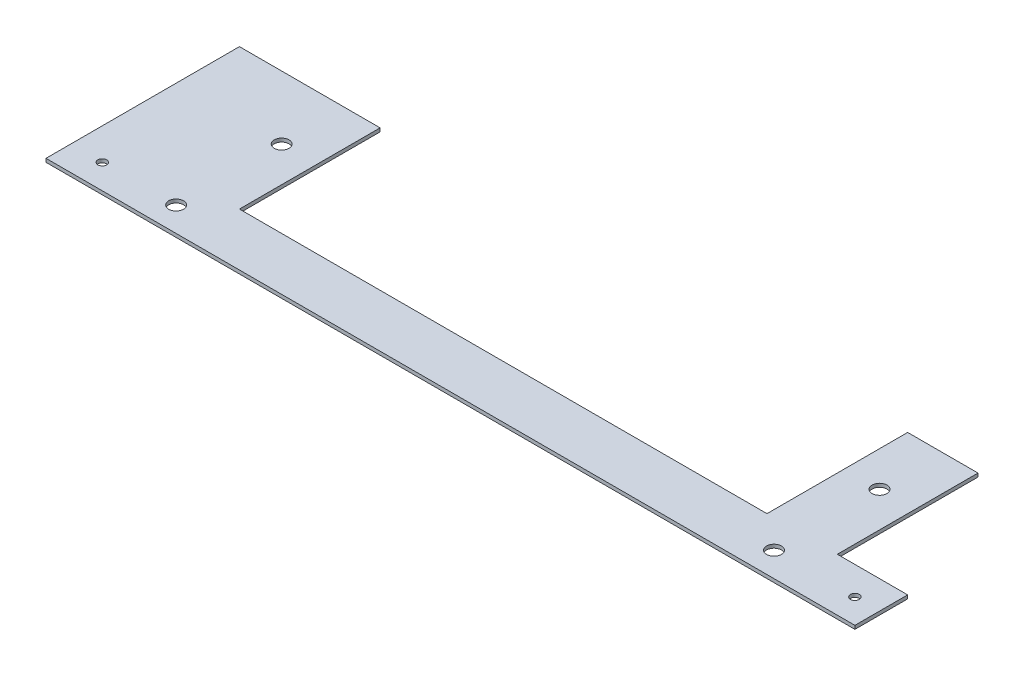
SolidWorks part; units mm, degrees
ref_plane "正面" through (0, 0, 0) normal (0, 0, 1) x (1, 0, 0)
ref_plane "平面" through (0, 0, 0) normal (0, 1, 0) x (1, 0, 0)
ref_plane "右側面" through (0, 0, 0) normal (1, 0, 0) x (0, 0, -1)
sketch "ｽｹｯﾁ1" plane through (0, 0, 0) normal (0, 0, 1) x (1, 0, 0)
  line L1 (0, 0) -> (230, 0)
  line L2 (0, 0) -> (0, 1)
  line L3 (0, 1) -> (230, 1)
  line L4 (230, 0) -> (230, 1)
  dimension "D1" = 1
  dimension "D2" = 230
extrude "ﾎﾞｽ - 押し出し1" add sketch "ｽｹｯﾁ1" along normal blind 15
hole_wizard "M3x0.5 ねじ穴1" positions "ｽｹｯﾁ2" profile "ｽｹｯﾁ3" tap size "M3x0.5" standard "JIS" end condition through all
sketch "ｽｹｯﾁ2" plane through (0, 0, 0) normal (0, -1, 0) x (-1, 0, 0)
  line L0 (0, -15) -> (0, 0) construction
  line L1 (-230, -15) -> (-230, 0) construction
  line L2 (-0.55, 0) -> (0.55, 0) construction
  point P0 (-9, -8)
  point P2 (-223, -8)
  point P9 (-230, -7.5)
  dimension "D1" = 9
  dimension "D2" = 7
  dimension "D3" = 8
  dimension "D4" = 8
sketch "ｽｹｯﾁ3" plane through (9, 0, 8) normal (1, 0, 0) x (0, 0, -1)
  line L0 (0, 0) -> (0, 1)
  line L1 (0, 1) -> (1.25, 1)
  line L2 (1.25, 1) -> (1.25, 0)
  line L5 (1.25, 0) -> (0, 0)
  line L11 (0, -6.35) -> (0, 107.95) construction
  dimension "次ｻｰﾌｪｽまでのねじ下穴ﾄﾞﾘﾙ直径" = 2.5
  dimension "次ｻｰﾌｪｽまでのねじ下穴ﾄﾞﾘﾙの深さ" = 1
cosmetic thread "穴のねじ山1" parameters "D2"=3
cosmetic thread "穴のねじ山2" parameters "D2"=3
hole_wizard "M5x0.8 ねじ穴1" positions "ｽｹｯﾁ4" profile "ｽｹｯﾁ5" tap size "M5x0.8" standard "JIS" end condition through all
sketch "ｽｹｯﾁ4" plane through (0, 1, 0) normal (0, 1, 0) x (1, 0, 0)
  line L0 (230, -15) -> (230, 0) construction
  line L1 (0, -15) -> (0, 0) construction
  line L2 (230, -15) -> (0, -15) construction
  point P0 (30, -8)
  point P2 (200, -8)
  dimension "D1" = 30
  dimension "D2" = 30
  dimension "D3" = 7
  dimension "D4" = 7
cosmetic thread "穴のねじ山3" parameters "D2"=5
cosmetic thread "穴のねじ山4" parameters "D2"=5
sketch "ｽｹｯﾁ5" plane through (30, 1, 8) normal (1, 0, 0) x (0, 0, 1)
  line L0 (0, 0) -> (0, 1)
  line L1 (0, 1) -> (2.1, 1)
  line L2 (2.1, 1) -> (2.1, 0)
  line L5 (2.1, 0) -> (0, 0)
  line L11 (0, -6.35) -> (0, 107.95) construction
  dimension "次ｻｰﾌｪｽまでのねじ下穴ﾄﾞﾘﾙ直径" = 4.2
  dimension "次ｻｰﾌｪｽまでのねじ下穴ﾄﾞﾘﾙの深さ" = 1
sketch "ｽｹｯﾁ10" plane through (0, 0, 0) normal (0, 0, -1) x (-1, 0, 0)
  line L0 (-230, 1) -> (0, 1) construction
  line L1 (-210, 1) -> (-190, 1)
  line L2 (-210, 1) -> (-210, 0)
  line L3 (-210, 0) -> (-190, 0)
  line L4 (-190, 1) -> (-190, 0)
  line L5 (0, 0) -> (-230, 0) construction
  line L6 (-230, 0) -> (-230, 1) construction
  point P10 (-230, 0.5)
  dimension "D1" = 20
  dimension "D2" = 20
extrude "ﾎﾞｽ - 押し出し3" add sketch "ｽｹｯﾁ10" along normal blind 40
sketch "ｽｹｯﾁ11" plane through (0, 0, 0) normal (0, 0, -1) x (-1, 0, 0)
  line L0 (0, 1) -> (0, 0) construction
  line L1 (0, 1) -> (-40, 1)
  line L2 (0, 1) -> (0, 0)
  line L3 (0, 0) -> (-40, 0)
  line L4 (-40, 1) -> (-40, 0)
  line L5 (0, 0) -> (-190, 0) construction
  dimension "D1" = 40
extrude "ﾎﾞｽ - 押し出し4" add sketch "ｽｹｯﾁ11" along normal blind 40
hole_wizard "M5x0.8 ねじ穴3" positions "ｽｹｯﾁ12" profile "ｽｹｯﾁ13" tap size "M5x0.8" standard "JIS" end condition through all
sketch "ｽｹｯﾁ12" plane through (0, 1, 0) normal (0, 1, 0) x (1, 0, 0)
  line L0 (40, 40) -> (40, 0) construction
  line L1 (190, 40) -> (190, 0) construction
  circle A0 centre (30, -8) radius 2.1 construction
  circle A1 centre (200, -8) radius 2.1 construction
  point P0 (30, 22)
  point P2 (200, 22)
  dimension "D2" = 30
  dimension "D1" = 10
  dimension "D3" = 30
  dimension "D4" = 10
sketch "ｽｹｯﾁ13" plane through (30, 1, -22) normal (1, 0, 0) x (0, 0, 1)
  line L0 (0, 0) -> (0, 1)
  line L1 (0, 1) -> (2.1, 1)
  line L2 (2.1, 1) -> (2.1, 0)
  line L5 (2.1, 0) -> (0, 0)
  line L11 (0, -6.35) -> (0, 107.95) construction
  dimension "次ｻｰﾌｪｽまでのねじ下穴ﾄﾞﾘﾙ直径" = 4.2
  dimension "次ｻｰﾌｪｽまでのねじ下穴ﾄﾞﾘﾙの深さ" = 1
cosmetic thread "穴のねじ山11" parameters "D2"=5
cosmetic thread "穴のねじ山12" parameters "D2"=5
